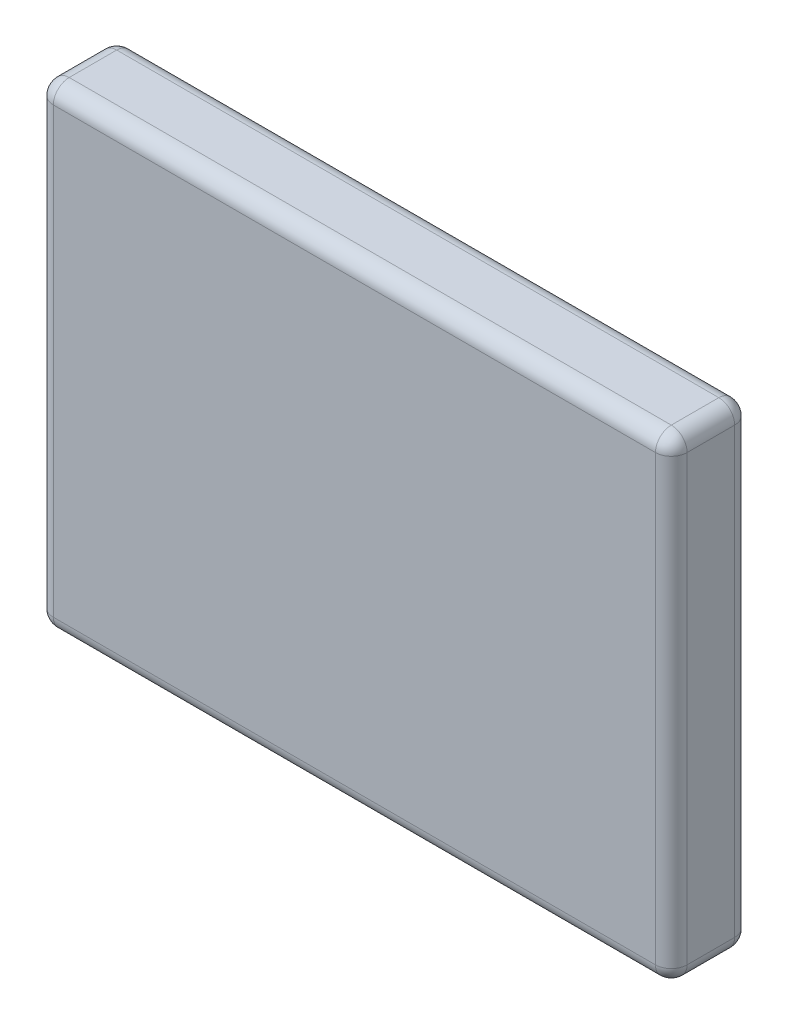
SolidWorks part; units mm, degrees
ref_plane "Front Plane" through (0, 0, 0) normal (0, 0, 1) x (1, 0, 0)
ref_plane "Top Plane" through (0, 0, 0) normal (0, 1, 0) x (1, 0, 0)
ref_plane "Right Plane" through (0, 0, 0) normal (1, 0, 0) x (0, 0, -1)
sketch "Sketch1" plane through (0, 0, 0) normal (0, 0, 1) x (1, 0, 0)
  line L1 (0, 0) -> (101.6, 0)
  line L2 (0, 0) -> (0, 76.2)
  line L3 (0, 76.2) -> (101.6, 76.2)
  line L4 (101.6, 0) -> (101.6, 76.2)
extrude "Boss-Extrude1" add sketch "Sketch1" along normal blind 12.7
fillet "Fillet1" radius 2.54 12 edges at (0, 38.1, 0) (50.8, 0, 0) (101.6, 38.1, 0) (50.8, 76.2, 0) (0, 38.1, 12.7) (50.8, 0, 12.7) (101.6, 38.1, 12.7) (50.8, 76.2, 12.7) (0, 76.2, 6.35) (101.6, 76.2, 6.35) (101.6, 0, 6.35) (0, 0, 6.35)
